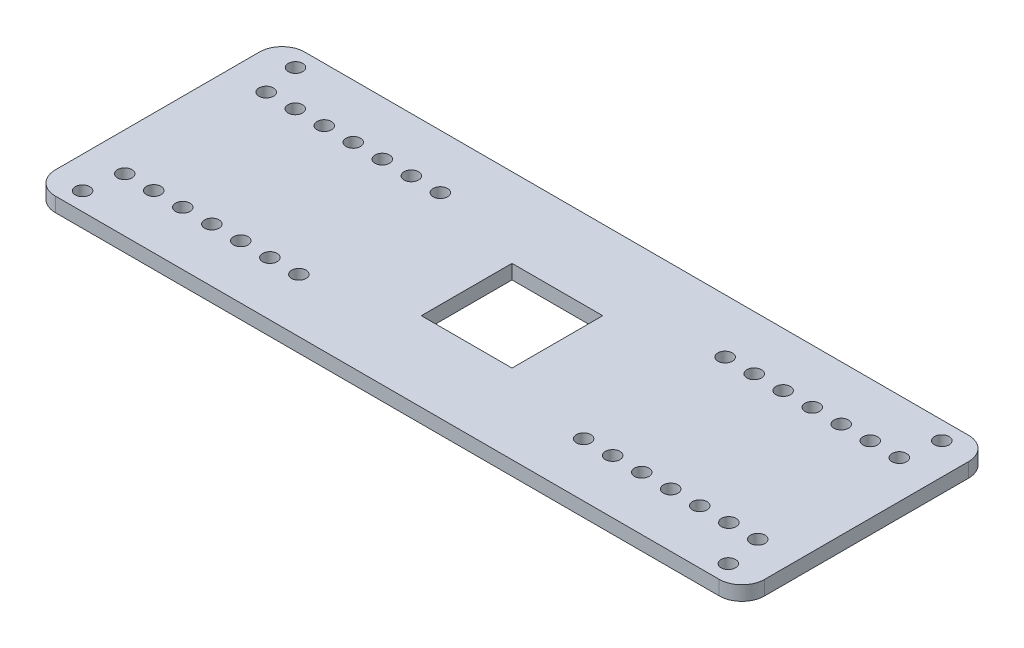
SolidWorks part; units mm, degrees
ref_plane "Front Plane" through (0, 0, 0) normal (0, 0, 1) x (1, 0, 0)
ref_plane "Top Plane" through (0, 0, 0) normal (0, 1, 0) x (1, 0, 0)
ref_plane "Right Plane" through (0, 0, 0) normal (1, 0, 0) x (0, 0, -1)
sketch "Sketch2" plane through (0, 0, 0) normal (0, 1, 0) x (1, 0, 0)
  line L1 (-78.2, 27.5) -> (78.2, 27.5)
  line L2 (-78.2, 27.5) -> (-78.2, -27.5)
  line L3 (-78.2, -27.5) -> (78.2, -27.5)
  line L4 (78.2, 27.5) -> (78.2, -27.5)
  line L5 (-78.2, 27.5) -> (78.2, -27.5) construction
  line L6 (-78.2, -27.5) -> (78.2, 27.5) construction
  point P0 (0, 0)
  dimension "D1" = 55
  dimension "D2" = 156.4
extrude "Boss-Extrude1" add sketch "Sketch2" along normal blind 3.175
ref_plane "Plane1" through (0, 0, 0) normal (0, 0, -1) x (-1, 0, 0)
sketch "Sketch5" plane through (0, 3.175, 0) normal (0, 1, 0) x (1, 0, 0)
  line L0 (-78.2, 0) -> (78.2, 0.1959) construction
  line L1 (-78.2, -27.5) -> (-71.2, -27.5) construction
  line L2 (-78.2, -27.5) -> (-78.2, -23.5) construction
  line L3 (-78.2, -23.5) -> (-71.2, -23.5) construction
  line L4 (-71.2, -27.5) -> (-71.2, -23.5) construction
  line L5 (-78.2, -27.5) -> (-71.2, -23.5) construction
  line L6 (-78.2, -23.5) -> (-71.2, -27.5) construction
  line L7 (-78.2, 27.5) -> (-78.2, -27.5) construction
  line L8 (78.2, -27.5) -> (78.2, 27.5) construction
  line L9 (0, 0.0979) -> (0, 27.5) construction
  line L10 (78.2, 27.5) -> (-78.2, 27.5) construction
  line L11 (0, 27.5) -> (0, -27.5) construction
  line L12 (-78.2, -27.5) -> (78.2, -27.5) construction
  circle A0 centre (-71.2, -23.5) radius 1.6
  circle A1 centre (-71.2589, 23.5175) radius 1.6
  circle A2 centre (71.2589, 23.5175) radius 1.6
  circle A3 centre (71.2, -23.5) radius 1.6
  point P4 (-74.7, -25.5)
  dimension "D2" = 3.2
  dimension "D1" = 7
  dimension "D3" = 4
extrude "Cut-Extrude3" cut sketch "Sketch5" against normal through all
sketch "Sketch6" plane through (0, 3.175, 0) normal (0, 1, 0) x (1, 0, 0)
  line L0 (78.2, 0) -> (-78.2, 0) construction
  line L1 (78.2, -27.5) -> (78.2, 27.5) construction
  line L2 (-78.2, 27.5) -> (-78.2, -27.5) construction
  line L3 (-78.2, 0) -> (0, 0) construction
  line L4 (0, 0) -> (0, -27.5) construction
  line L5 (-78.2, -27.5) -> (78.2, -27.5) construction
  line L6 (0, -27.5) -> (0, 27.5) construction
  line L7 (78.2, 27.5) -> (-78.2, 27.5) construction
  circle A0 centre (69.8, -15.6) radius 1.6 construction
  circle A1 centre (63.4, -15.6) radius 1.6 construction
  circle A2 centre (57, -15.6) radius 1.6 construction
  circle A3 centre (50.6, -15.6) radius 1.6 construction
  circle A4 centre (37.8, -15.6) radius 1.6 construction
  circle A5 centre (31.4, -15.6) radius 1.6 construction
  circle A6 centre (69.8, -15.6) radius 1.6
  circle A7 centre (63.4, -15.6) radius 1.6
  circle A8 centre (57, -15.6) radius 1.6
  circle A9 centre (50.6, -15.6) radius 1.6
  circle A10 centre (37.8, -15.6) radius 1.6
  circle A11 centre (31.4, -15.6) radius 1.6
  circle A12 centre (44.2, -15.6) radius 1.6 construction
  circle A13 centre (44.2, -15.6) radius 1.6
  circle A14 centre (31.4, 15.6) radius 1.6
  circle A15 centre (37.8, 15.6) radius 1.6
  circle A16 centre (44.2, 15.6) radius 1.6
  circle A17 centre (50.6, 15.6) radius 1.6
  circle A18 centre (57, 15.6) radius 1.6
  circle A19 centre (63.4, 15.6) radius 1.6
  circle A20 centre (69.8, 15.6) radius 1.6
  circle A21 centre (-31.4, 15.6) radius 1.6
  circle A22 centre (-37.8, 15.6) radius 1.6
  circle A23 centre (-44.2, 15.6) radius 1.6
  circle A24 centre (-50.6, 15.6) radius 1.6
  circle A25 centre (-57, 15.6) radius 1.6
  circle A26 centre (-63.4, 15.6) radius 1.6
  circle A27 centre (-69.8, 15.6) radius 1.6
  circle A28 centre (-31.4, -15.6) radius 1.6
  circle A29 centre (-37.8, -15.6) radius 1.6
  circle A30 centre (-44.2, -15.6) radius 1.6
  circle A31 centre (-50.6, -15.6) radius 1.6
  circle A32 centre (-57, -15.6) radius 1.6
  circle A33 centre (-63.4, -15.6) radius 1.6
  circle A34 centre (-69.8, -15.6) radius 1.6
extrude "Cut-Extrude4" cut sketch "Sketch6" against normal through all
sketch "Sketch7" plane through (0, 3.175, 0) normal (0, 1, 0) x (1, 0, 0)
  line L1 (-10, 10) -> (10, 10)
  line L2 (-10, 10) -> (-10, -10)
  line L3 (-10, -10) -> (10, -10)
  line L4 (10, 10) -> (10, -10)
  line L5 (-10, 10) -> (10, -10) construction
  line L6 (-10, -10) -> (10, 10) construction
  point P0 (0, 0)
  dimension "D1" = 20
  dimension "D2" = 20
extrude "Cut-Extrude5" cut sketch "Sketch7" against normal through all
fillet "Fillet1" radius 5 4 edges at (-78.2, 1.5875, -27.5) (-78.2, 1.5875, 27.5) (78.2, 1.5875, -27.5) (78.2, 1.5875, 27.5)
